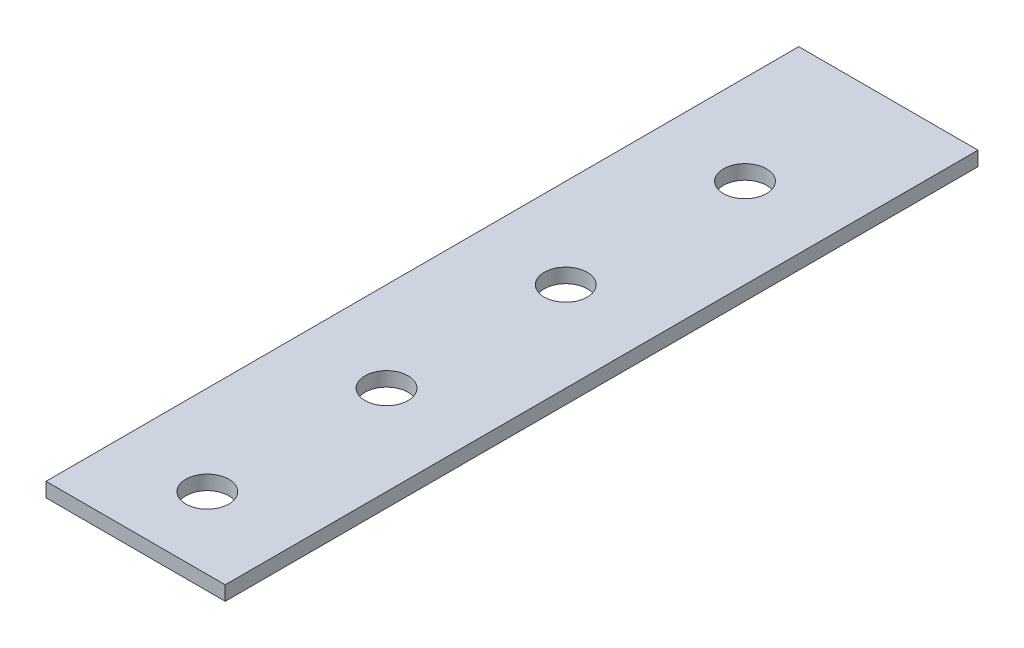
SolidWorks part; units mm, degrees
ref_plane "Front Plane" through (0, 0, 0) normal (0, 0, 1) x (1, 0, 0)
ref_plane "Top Plane" through (0, 0, 0) normal (0, 1, 0) x (1, 0, 0)
ref_plane "Right Plane" through (0, 0, 0) normal (1, 0, 0) x (0, 0, -1)
sketch "Sketch1" plane through (0, 0, 0) normal (0, 1, 0) x (1, 0, 0)
  line L1 (-12.5, -52.5) -> (12.5, -52.5)
  line L2 (-12.5, -52.5) -> (-12.5, 52.5)
  line L3 (-12.5, 52.5) -> (12.5, 52.5)
  line L4 (12.5, -52.5) -> (12.5, 52.5)
  line L5 (-12.5, -52.5) -> (12.5, 52.5) construction
  line L6 (-12.5, 52.5) -> (12.5, -52.5) construction
  point P0 (0, 0)
  dimension "D1" = 105
  dimension "D2" = 25
extrude "Boss-Extrude1" add sketch "Sketch1" along normal blind 2
sketch "Sketch2" plane through (0, 2, 0) normal (0, 1, 0) x (1, 0, 0)
  line L0 (-12.5, -52.5) -> (12.5, -52.5) construction
  line L1 (-12.5, 52.5) -> (-12.5, -52.5) construction
  circle A0 centre (0, -42.5) radius 3
  circle A1 centre (0, -17.5) radius 3
  circle A2 centre (0, 7.5) radius 3
  circle A3 centre (0, 32.5) radius 3
  point P11 (0, 0)
  point P13 (-32.075, -44.1463)
  dimension "D1" = 6
  dimension "D2" = 6
  dimension "D3" = 6
  dimension "D4" = 6
  dimension "D5" = 10
  dimension "D6" = 12.5
  dimension "D7" = 25
  dimension "D8" = 12.5
  dimension "D9" = 25
  dimension "D10" = 12.5
  dimension "D11" = 12.5
  dimension "D12" = 25
extrude "Cut-Extrude1" cut sketch "Sketch2" against normal through all
